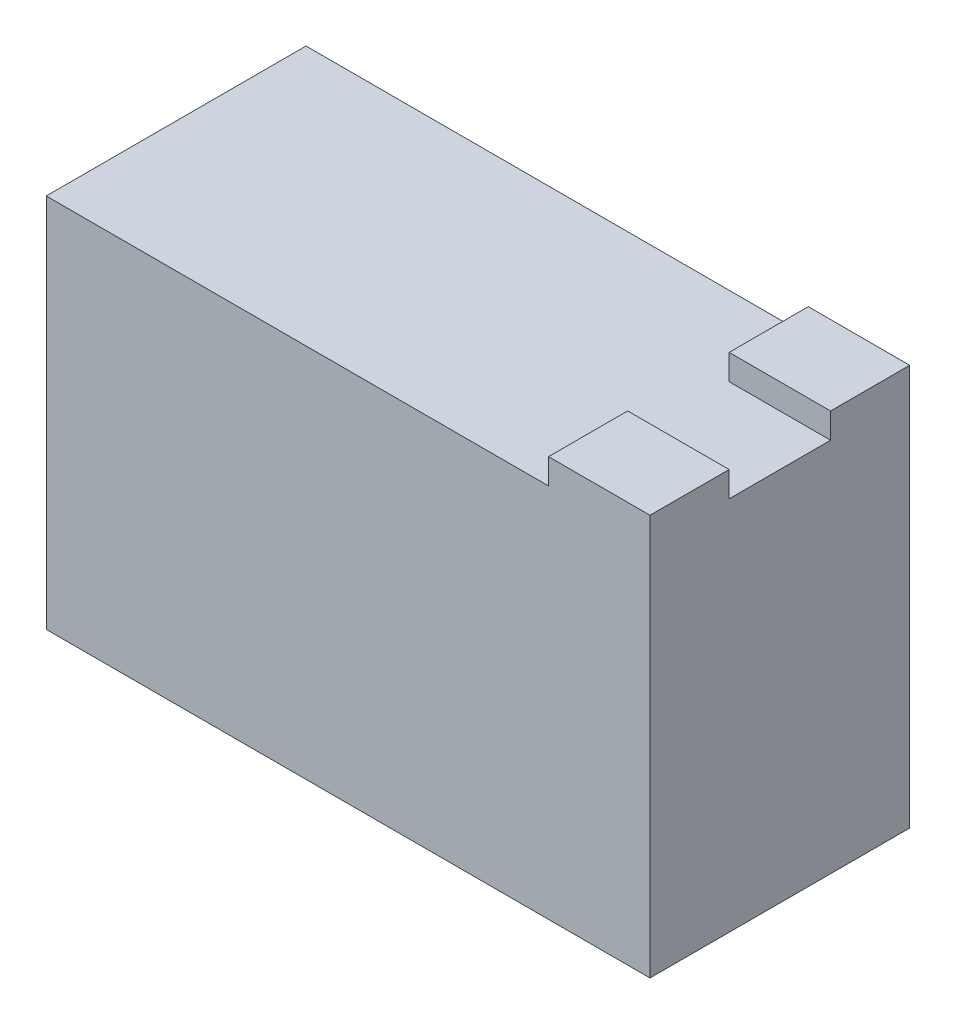
SolidWorks part; units mm, degrees
ref_plane "Front Plane" through (0, 0, 0) normal (0, 0, 1) x (1, 0, 0)
ref_plane "Top Plane" through (0, 0, 0) normal (0, 1, 0) x (1, 0, 0)
ref_plane "Right Plane" through (0, 0, 0) normal (1, 0, 0) x (0, 0, -1)
sketch "Sketch1" plane through (0, 0, 0) normal (0, 1, 0) x (1, 0, 0)
  line L1 (75.565, -32.512) -> (-75.565, -32.512)
  line L2 (75.565, -32.512) -> (75.565, 32.512)
  line L3 (75.565, 32.512) -> (-75.565, 32.512)
  line L4 (-75.565, -32.512) -> (-75.565, 32.512)
  line L5 (75.565, -32.512) -> (-75.565, 32.512) construction
  line L6 (75.565, 32.512) -> (-75.565, -32.512) construction
  point P0 (0, 0)
  dimension "D1" = 151.13
  dimension "D2" = 65.024
extrude "Boss-Extrude1" add sketch "Sketch1" along normal blind 93.98
sketch "Sketch2" plane through (0, 93.98, 0) normal (0, 1, 0) x (1, 0, 0)
  line L0 (-75.565, -32.512) -> (75.565, -32.512) construction
  line L1 (75.565, 32.512) -> (50.165, 32.512)
  line L2 (75.565, 32.512) -> (75.565, 12.7)
  line L3 (75.565, -32.512) -> (50.165, -32.512)
  line L4 (50.165, 32.512) -> (50.165, 12.7)
  line L5 (62.865, -32.512) -> (62.865, 32.512) construction
  line L6 (50.165, -12.7) -> (50.165, -32.512)
  line L7 (50.165, -12.7) -> (75.565, -12.7)
  line L9 (50.165, 12.7) -> (75.565, 12.7)
  line L11 (50.165, -12.7) -> (75.565, 12.7) construction
  line L12 (50.165, 12.7) -> (75.565, -12.7) construction
  line L13 (75.565, -12.7) -> (75.565, -32.512)
  point P9 (62.865, 0)
  dimension "D1" = 25.4
  dimension "D2" = 25.4
extrude "Boss-Extrude2" add sketch "Sketch2" along normal blind 6.35
